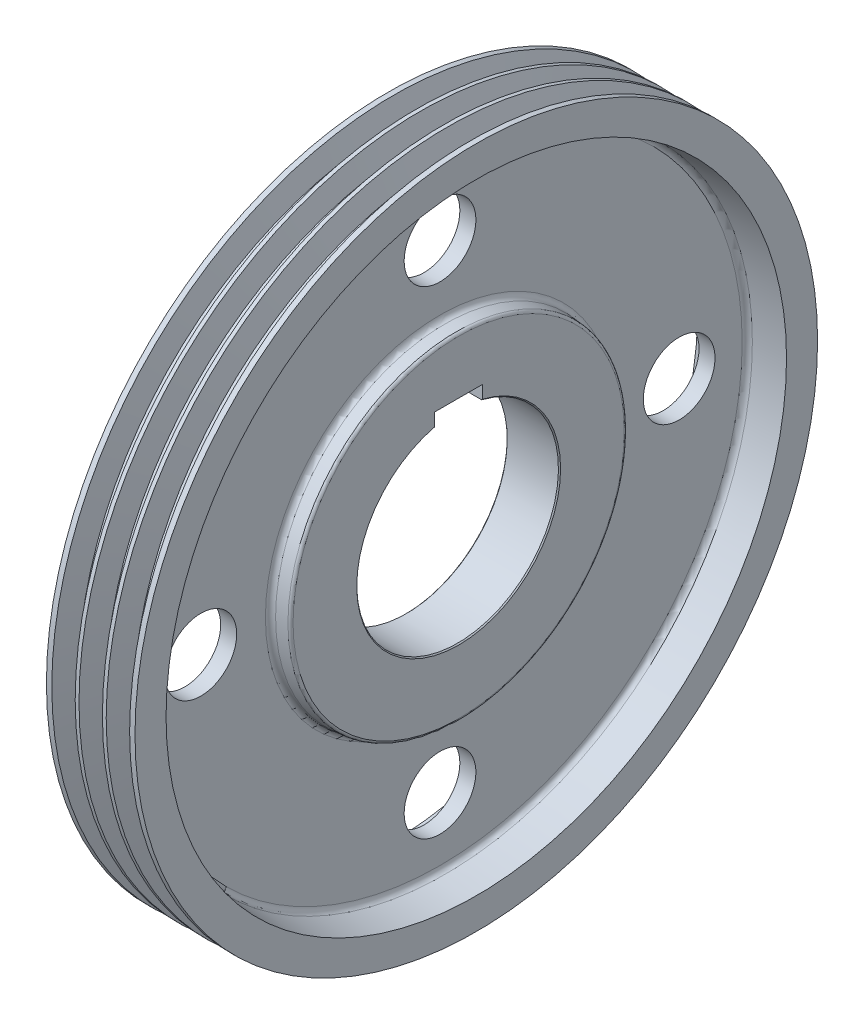
SolidWorks part; units mm, degrees
ref_plane "前视基准面" through (0, 0, 0) normal (0, 0, 1) x (1, 0, 0)
ref_plane "上视基准面" through (0, 0, 0) normal (0, 1, 0) x (1, 0, 0)
ref_plane "右视基准面" through (0, 0, 0) normal (1, 0, 0) x (0, 0, -1)
sketch "草图1" plane through (0, 0, 0) normal (0, 0, 1) x (1, 0, 0)
  line L0 (0, 0) -> (64.8368, 0) construction
  line L1 (16.5, 94.5) -> (16.5, 157.5)
  line L2 (0, 319.8) -> (83, 319.8)
  line L3 (83, 319.8) -> (83, 290.7)
  line L4 (16.5, 157.5) -> (-12.5, 157.5) construction
  line L5 (34, 159.0311) -> (34, 287.7254)
  line L6 (66.5, 94.5) -> (16.5, 94.5)
  line L7 (5.0325, 319.8) -> (10.8719, 300.7) construction
  line L8 (10.8719, 300.7) -> (21.1281, 300.7) construction
  line L9 (21.1281, 300.7) -> (26.9675, 319.8) construction
  line L10 (0, 315) -> (83, 315) construction
  line L11 (16, 300.7) -> (16, 94.5) construction
  line L12 (44, 290.7) -> (0, 290.7) construction
  line L13 (83, 290.7) -> (79, 290.7) construction
  line L14 (49, 287.7254) -> (49, 159.0311)
  line L15 (22.5, 157.5) -> (66.5, 157.5) construction
  line L16 (41.5, 94.5) -> (41.5, 319.8) construction
  line L17 (66.5, 157.5) -> (66.5, 94.5)
  line L18 (0, 290.7) -> (0, 319.8)
  line L19 (34, 257.7) -> (49, 257.7) construction
  line L20 (34, 190.5) -> (49, 190.5) construction
  line L21 (83, 290.7) -> (83, 257.7) construction
  line L22 (83, 257.7) -> (49, 257.7) construction
  line L23 (49, 190.5) -> (66.5, 190.5) construction
  line L24 (66.5, 190.5) -> (66.5, 157.5) construction
  line L25 (49, 287.7254) -> (83, 290.7)
  line L26 (34, 287.7254) -> (0, 290.7)
  line L27 (34, 159.0311) -> (16.5, 157.5)
  line L28 (49, 159.0311) -> (66.5, 157.5)
  point P17 (6.5, 315)
  point P18 (25.5, 315)
  dimension "d2" = 581.4
  dimension "L" = 50
  dimension "B" = 83
  dimension "d" = 189
  dimension "d1" = 315
  dimension "D3" = 5
  dimension "D4" = 5
  dimension "dd" = 630
  dimension "f" = 16
  dimension "槽轮角" = 34
  dimension "bd" = 19
  dimension "hf" = 14.3
  dimension "ha" = 4.8
  dimension "da" = 639.6
  dimension "S" = 15
  dimension "S2" = 33
revolve "旋转1" add sketch "草图1" angle 360 about L0
sketch "草图2" plane through (0, 0, 0) normal (0, 0, 1) x (1, 0, 0)
  line L0 (21.1281, 300.7) -> (26.9675, 319.8) construction
  line L1 (10.8719, 300.7) -> (21.1281, 300.7) construction
  line L2 (5.0325, 319.8) -> (10.8719, 300.7) construction
  line L3 (21.1281, 300.7) -> (26.9675, 319.8)
  line L4 (10.8719, 300.7) -> (21.1281, 300.7)
  line L5 (5.0325, 319.8) -> (10.8719, 300.7)
  line L6 (5.0325, 319.8) -> (26.9675, 319.8)
  line L7 (0, 0) -> (123, 0) construction
revolve "切除-旋转1" cut sketch "草图2" angle 360 about L7
pattern_linear "轮槽数" count 3 spacing 25.5 along (1, 0, 0) of "切除-旋转1"
chamfer "倒角1" distance 1 2 edges at (16.5, 0, 94.5) (66.5, 0, 94.5)
sketch "草图4" plane through (16.5, 0, 0) normal (-1, 0, 0) x (0, 0, 1)
  line L1 (-22.5, 91.7824) -> (22.5, 91.7824)
  line L2 (-22.5, 91.7824) -> (-22.5, 104.9)
  line L3 (-22.5, 104.9) -> (22.5, 104.9)
  line L4 (22.5, 91.7824) -> (22.5, 104.9)
  circle A0 centre (0, 0) radius 94.5 construction
  point P6 (12.1, 104.9)
  dimension "键槽高度" = 104.9
  dimension "键槽宽度" = 45
  dimension "t1" = 10.4
extrude "切除-拉伸1" cut sketch "草图4" against normal through all
fillet "圆角1" radius 5 4 edges at (49, 0, 287.7254) (34, 0, 159.0311) (34, 0, 287.7254) (49, 0, 159.0311)
fillet "圆角2" radius 2.5 2 edges at (66.5, 0, 157.5) (16.5, 0, 157.5)
sketch "草图5" plane through (0, 0, 0) normal (1, 0, 0) x (0, 0, -1)
  line L0 (0, 300.7) -> (0, 94.5) construction
  circle A0 centre (0, 224.1) radius 33.6
extrude "切除-拉伸2" cut sketch "草图5" along normal through all
pattern_circular "圆孔个数" count 4 over 360 about axis through (0, 0, 0) along (1, 0, 0) of "切除-拉伸2"
